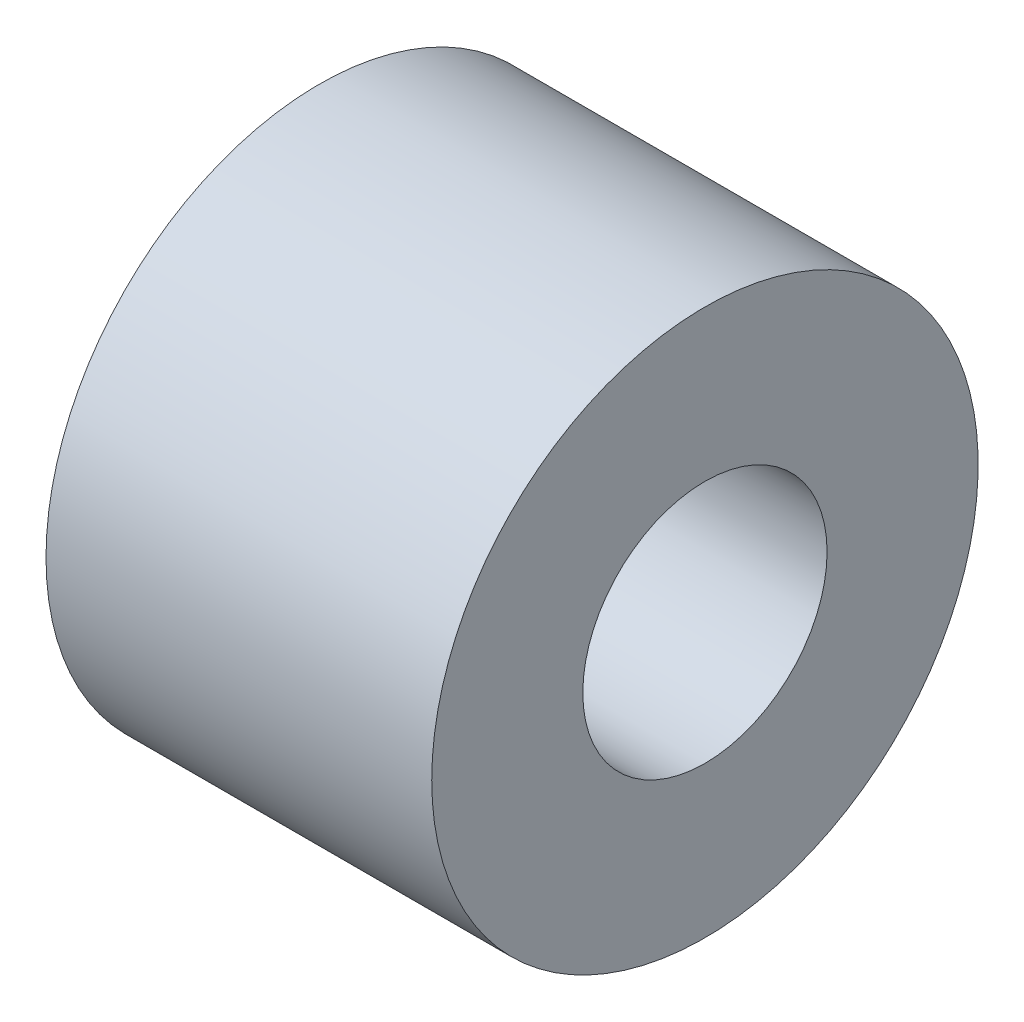
SolidWorks part; units mm, degrees
material "6061 Alloy"
ref_plane "Front Plane" through (0, 0, 0) normal (0, 0, 1) x (1, 0, 0)
ref_plane "Top Plane" through (0, 0, 0) normal (0, 1, 0) x (1, 0, 0)
ref_plane "Right Plane" through (0, 0, 0) normal (1, 0, 0) x (0, 0, -1)
sketch "Croquis1" plane through (0, 0, 0) normal (1, 0, 0) x (0, 0, -1)
  circle A0 centre (0, 0) radius 5.3975
  circle A1 centre (0, 0) radius 2.413
  dimension "D1" = 10.795
  dimension "D2" = 4.826
extrude "Saliente-Extruir1" add sketch "Croquis1" along normal mid plane 7.62
